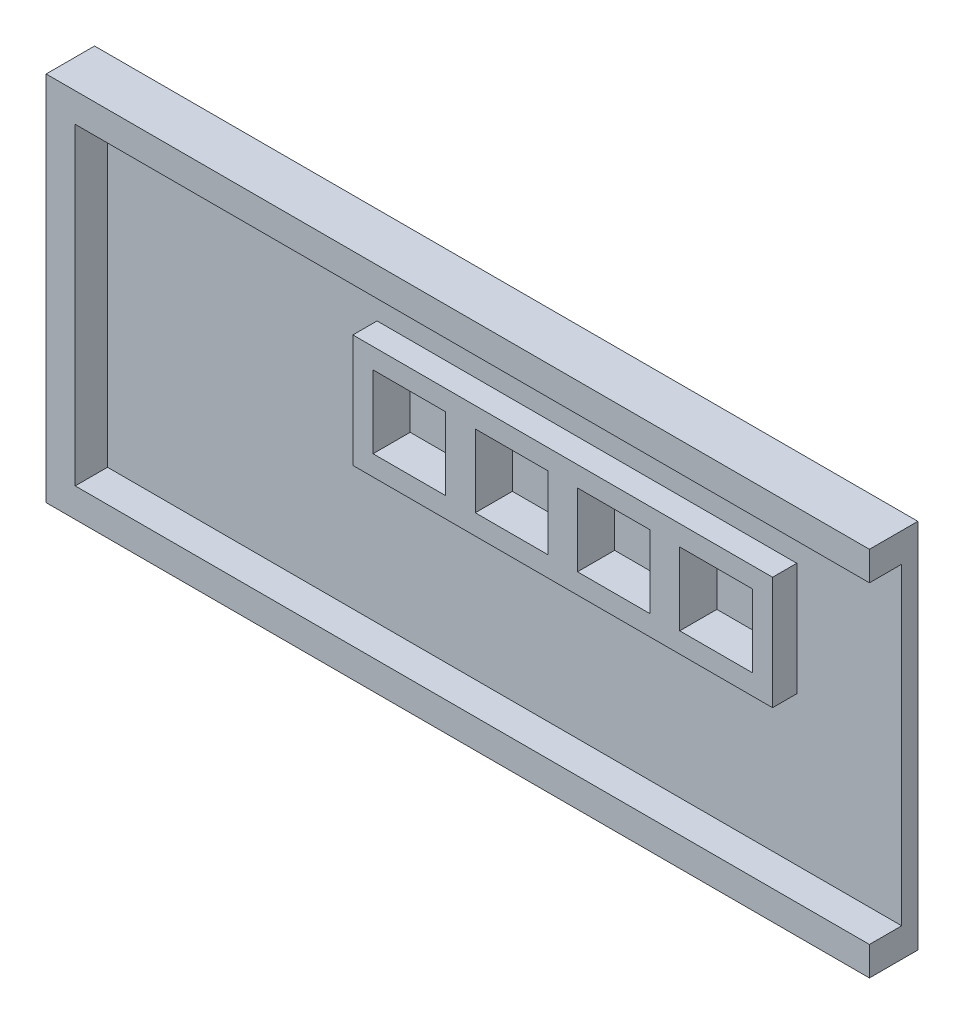
SolidWorks part; units mm, degrees
ref_plane "Спереди" through (0, 0, 0) normal (0, 0, 1) x (1, 0, 0)
ref_plane "Сверху" through (0, 0, 0) normal (0, 1, 0) x (1, 0, 0)
ref_plane "Справа" through (0, 0, 0) normal (1, 0, 0) x (0, 0, -1)
sketch "Sketch1" plane through (0, 0, 0) normal (0, 0, 1) x (1, 0, 0)
  line L1 (0, 0) -> (-51, 0)
  line L2 (0, 0) -> (0, 23)
  line L3 (0, 23) -> (-51, 23)
  line L4 (-51, 0) -> (-51, 23)
  dimension "D1" = 23
  dimension "D2" = 51
extrude "Boss-Extrude1" add sketch "Sketch1" along normal blind 1
sketch "Sketch2" plane through (0, 0, 1) normal (0, 0, 1) x (1, 0, 0)
  line L0 (0, 0) -> (0, 23) construction
  line L1 (-51, 23) -> (0, 23)
  line L2 (-51, 23) -> (-51, 21.2)
  line L3 (-49.2, 21.2) -> (0, 21.2)
  line L4 (0, 23) -> (0, 21.2)
  line L6 (-51, 0) -> (0, 0)
  line L7 (-51, 0) -> (-51, 1.8)
  line L8 (-49.2, 1.8) -> (0, 1.8)
  line L9 (0, 0) -> (0, 1.8)
  line L11 (-51, 21.2) -> (-51, 1.8)
  line L13 (-49.2, 21.2) -> (-49.2, 1.8)
  dimension "D1" = 1.8
  dimension "D2" = 1.8
  dimension "D3" = 1.8
extrude "Boss-Extrude2" add sketch "Sketch2" along normal blind 2
sketch "Sketch3" plane through (0, 0, 1) normal (0, 0, 1) x (1, 0, 0)
  line L0 (-51, 23) -> (-51, 0) construction
  line L1 (-32.5, 18) -> (-6.5, 18)
  line L2 (-32.5, 18) -> (-32.5, 11)
  line L3 (-32.5, 11) -> (-6.5, 11)
  line L4 (-6.5, 18) -> (-6.5, 11)
  line L5 (0, 23) -> (-51, 23) construction
  dimension "D1" = 7
  dimension "D2" = 26
  dimension "D3" = 18.5
  dimension "D4" = 5
extrude "Boss-Extrude3" add sketch "Sketch3" along normal blind 1.5
sketch "Sketch4" plane through (0, 0, 2.5) normal (0, 0, 1) x (1, 0, 0)
  line L0 (-32.5, 18) -> (-32.5, 11) construction
  line L1 (-31.25, 16.75) -> (-26.75, 16.75)
  line L2 (-31.25, 16.75) -> (-31.25, 12.25)
  line L3 (-31.25, 12.25) -> (-26.75, 12.25)
  line L4 (-26.75, 16.75) -> (-26.75, 12.25)
  line L5 (-24.9167, 16.75) -> (-20.4167, 16.75)
  line L6 (-24.9167, 16.75) -> (-24.9167, 12.25)
  line L7 (-24.9167, 12.25) -> (-20.4167, 12.25)
  line L8 (-20.4167, 16.75) -> (-20.4167, 12.25)
  line L9 (-18.5833, 16.75) -> (-14.0833, 16.75)
  line L10 (-18.5833, 16.75) -> (-18.5833, 12.25)
  line L11 (-18.5833, 12.25) -> (-14.0833, 12.25)
  line L12 (-14.0833, 16.75) -> (-14.0833, 12.25)
  line L13 (-12.25, 16.75) -> (-7.75, 16.75)
  line L14 (-12.25, 16.75) -> (-12.25, 12.25)
  line L15 (-12.25, 12.25) -> (-7.75, 12.25)
  line L16 (-7.75, 16.75) -> (-7.75, 12.25)
  line L17 (-32.5, 18) -> (-32.5, 11) construction
  line L19 (-6.5, 18) -> (-32.5, 18) construction
  line L21 (-6.5, 11) -> (-6.5, 18) construction
  point P4 (-31.25, 14.5)
  point P7 (-32.5, 14.5)
  point P22 (-8.1608, 12.3764)
  point P23 (0, 0)
  dimension "D1" = 4.5
  dimension "D2" = 4
  dimension "D3" = 1.25
  dimension "D4" = 1.25
  dimension "D5" = 1.25
extrude "Cut-Extrude1" cut sketch "Sketch4" against normal blind 2.3
equation "\"D2@Sketch2\"=\"D1@Sketch2\""
equation "\"D3@Sketch2\"=\"D1@Sketch2\""
